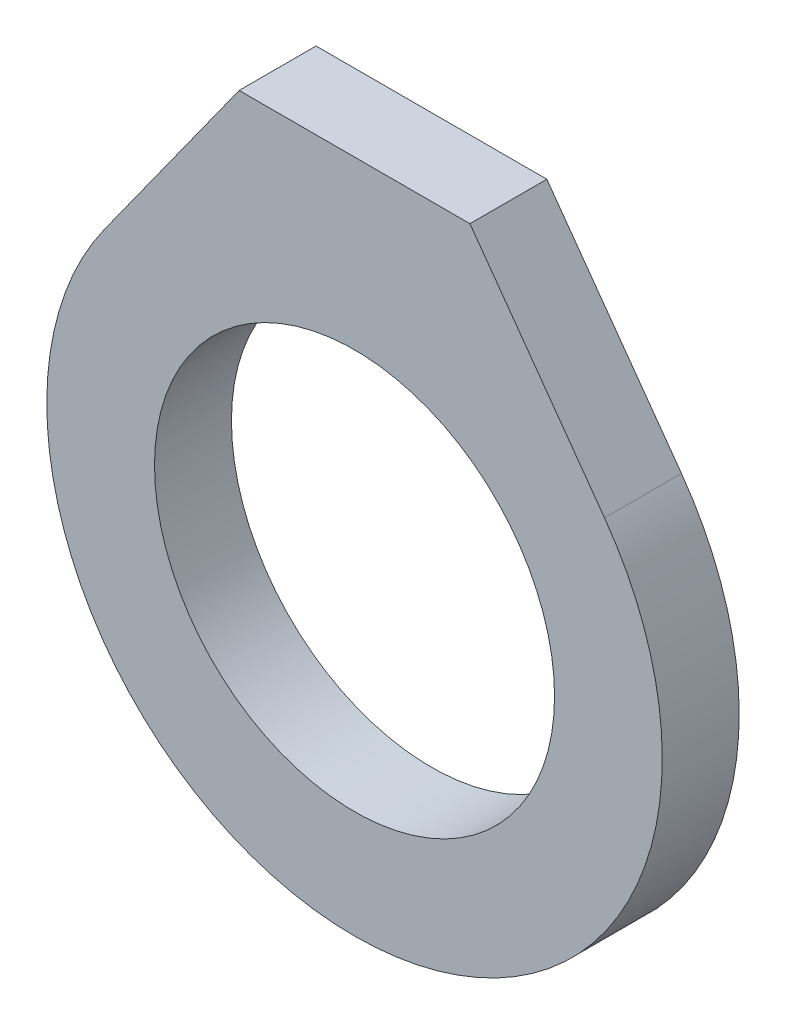
SolidWorks part; units mm, degrees
ref_plane "Front Plane" through (0, 0, 0) normal (0, 0, 1) x (1, 0, 0)
ref_plane "Top Plane" through (0, 0, 0) normal (0, 1, 0) x (1, 0, 0)
ref_plane "Right Plane" through (0, 0, 0) normal (1, 0, 0) x (0, 0, -1)
sketch "Sketch1" plane through (0, 0, 0) normal (0, 0, 1) x (1, 0, 0)
  line L0 (-32.4945, 23.3261) -> (-15, 47.697)
  line L1 (-15, 47.697) -> (15, 47.697)
  line L2 (15, 47.697) -> (32.4945, 23.3261)
  arc A0 (-32.4945, 23.3261) -> (32.4945, 23.3261) centre (0, 0) ccw
  circle A1 centre (0, 0) radius 26
  point P8 (0, 47.697)
  dimension "D1" = 80
  dimension "D2" = 52
  dimension "D3" = 30
  dimension "D4" = 30
extrude "Boss-Extrude1" add sketch "Sketch1" along normal mid plane 10
